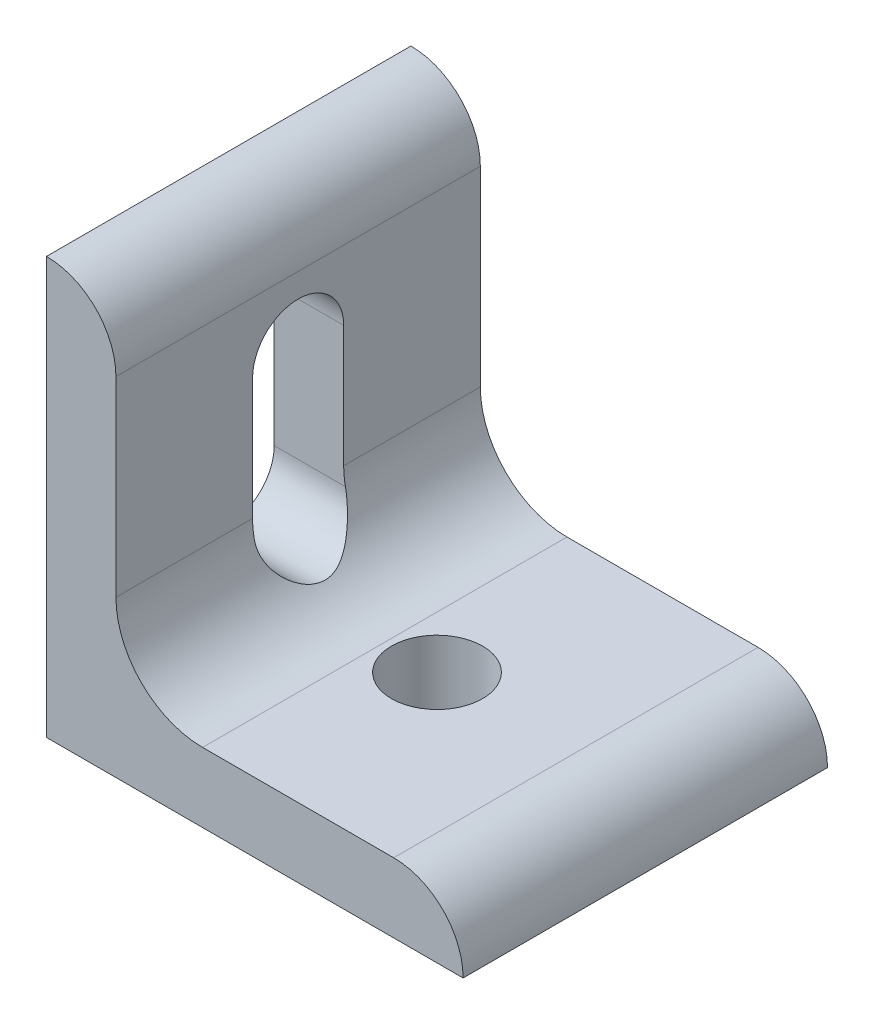
SolidWorks part; units mm, degrees
ref_plane "Front Plane" through (0, 0, 0) normal (0, 0, 1) x (1, 0, 0)
ref_plane "Top Plane" through (0, 0, 0) normal (0, 1, 0) x (1, 0, 0)
ref_plane "Right Plane" through (0, 0, 0) normal (1, 0, 0) x (0, 0, -1)
sketch "Sketch1" plane through (0, 0, 0) normal (0, 0, 1) x (1, 0, 0)
  line L0 (19.05, -19.05) -> (-19.05, -19.05) construction
  line L1 (19.05, -19.05) -> (19.05, -12.7) construction
  line L2 (-19.05, -19.05) -> (-19.05, 19.05) construction
  point P0 (-19.05, 0)
  point P3 (0, -19.05)
  dimension "Length" = 38.1
  dimension "Thickness" = 6.35
sketch "Sketch2" plane through (0, 0, 0) normal (1, 0, 0) x (0, 0, -1)
  line L0 (-16.6624, -19.05) -> (16.6624, -19.05) construction
  line L2 (0, 6.35) -> (0, -6.35) construction
  line L3 (0, -19.05) -> (0, 19.05) construction
  line L4 (4.1656, 6.35) -> (-4.1656, 6.35) construction
  point P4 (0, -19.05)
  point P12 (0, 6.35)
  dimension "Width" = 33.3248
  dimension "Bottom to Slot" = 12.7
  dimension "Slot Width" = 12.7
  dimension "Slot Dia" = 8.3312
sketch "Sketch3" plane through (0, 0, 0) normal (0, 1, 0) x (1, 0, 0)
  line L0 (-4.1656, 0) -> (4.1656, 0) construction
  line L1 (19.05, 0) -> (-19.05, 0) construction
  point P5 (0, 0)
  dimension "Hole Dia" = 8.3312
sketch "Sketch4" plane through (0, 0, 0) normal (0, 0, 1) x (1, 0, 0)
  line L0 (-19.05, 19.05) -> (-19.05, -19.05)
  line L1 (-19.05, -19.05) -> (19.05, -19.05)
  line L2 (12.7, -12.7) -> (-4.7752, -12.7)
  line L3 (-12.7, -4.7752) -> (-12.7, 12.7)
  arc A0 (-4.7752, -12.7) -> (-12.7, -4.7752) centre (-4.7752, -4.7752) cw
  arc A1 (12.7, -12.7) -> (19.05, -19.05) centre (12.7, -19.05) cw
  arc A2 (-12.7, 12.7) -> (-19.05, 19.05) centre (-19.05, 12.7) ccw
  dimension "D1" = 7.9248
extrude "Boss-Extrude1" add sketch "Sketch4" against normal up to vertex (16.6624 mm away) and the other way up to vertex (16.6624 mm away) up to point (0, -19.05, -16.6624) other way up to point (0, -19.05, 16.6624)
sketch "Sketch5" plane through (-12.7, 0, 0) normal (1, 0, 0) x (0, 0, -1)
  line L0 (0, 6.35) -> (0, -6.35) construction
  line L1 (4.1656, 6.35) -> (-4.1656, 6.35) construction
  line L2 (4.1656, 6.35) -> (4.1656, -6.35)
  line L3 (-4.1656, 6.35) -> (-4.1656, -6.35)
  arc A0 (4.1656, 6.35) -> (-4.1656, 6.35) centre (0, 6.35) ccw
  arc A1 (-4.1656, -6.35) -> (4.1656, -6.35) centre (0, -6.35) ccw
  point P5 (0, 0)
extrude "Cut-Extrude1" cut sketch "Sketch5" against normal through all both and the other way through all
sketch "Sketch6" plane through (0, -12.7, 0) normal (0, 1, 0) x (1, 0, 0)
  line L0 (19.05, 0) -> (-19.05, 0) construction
  circle A0 centre (0, 0) radius 4.1656
extrude "Cut-Extrude2" cut sketch "Sketch6" against normal through all
